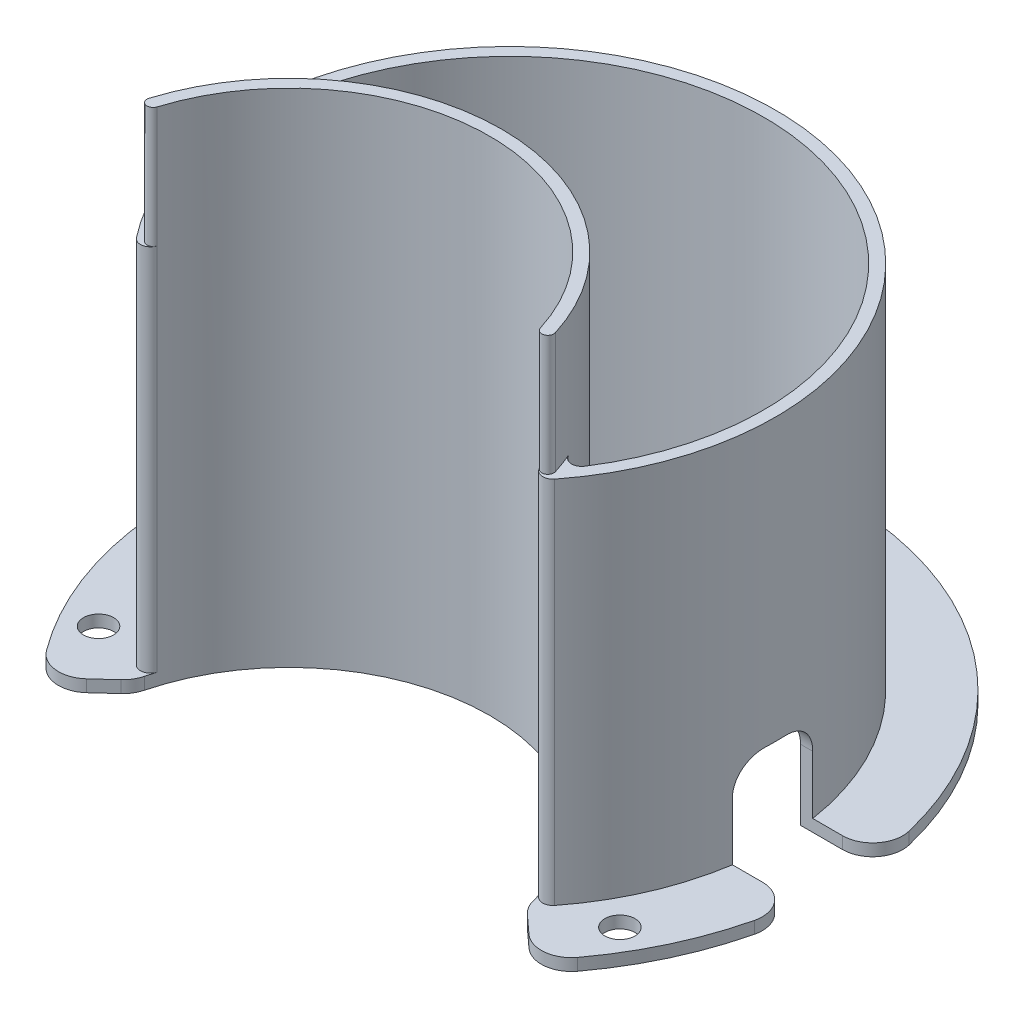
SolidWorks part; units mm, degrees
material "ABS"
ref_plane "Plan de face" through (0, 0, 0) normal (0, 0, 1) x (1, 0, 0)
ref_plane "Plan de dessus" through (0, 0, 0) normal (0, 1, 0) x (1, 0, 0)
ref_plane "Plan de droite" through (0, 0, 0) normal (1, 0, 0) x (0, 0, -1)
sketch "Esquisse1" plane through (0, 0, 0) normal (0, 1, 0) x (1, 0, 0)
  arc A0 (19.5688, -17.8693) -> (-19.5688, -17.8693) centre (0, 0) ccw
  arc A1 (19.5688, -17.8693) -> (-19.5688, -17.8693) centre (0, -22) ccw
  dimension "D1" = 53
  dimension "D2" = 2
  dimension "D3" = 40
extrude "Extru.-Mince1" add sketch "Esquisse1" along normal blind 38 thin thin type one direction reverse wall 1.2
sketch "Esquisse2" plane through (0, 0, 0) normal (0, 1, 0) x (1, 0, 0)
  line L0 (-19.5688, -17.8693) -> (-24.3687, -22.2524)
  line L1 (19.5688, -17.8693) -> (24.3687, -22.2524)
  arc A0 (19.5688, -17.8693) -> (-19.5688, -17.8693) centre (0, 0) ccw construction
  arc A1 (19.5688, -17.8693) -> (-19.5688, -17.8693) centre (0, 0) ccw
  arc A2 (24.3687, -22.2524) -> (-24.3687, -22.2524) centre (0, 0) ccw
  dimension "D1" = 33
extrude "Boss.-Extru.1" add sketch "Esquisse2" along normal blind 1.2
fillet "Congé1" radius 1 4 edges at (19.5688, 19.6, 17.8693) (-19.5688, 19.6, 17.8693) (20.1244, 19, 15.333) (-20.1244, 19, 15.333)
sketch "Esquisse3" plane through (0, 38, 0) normal (0, 1, 0) x (1, 0, 0)
  line L0 (0, 0) -> (0, -22) construction
  arc A0 (20.2411, -15.6962) -> (19.0954, -16.053) centre (19.6682, -15.8746) cw
  arc A1 (19.0954, -16.053) -> (-19.0954, -16.053) centre (0, -22) ccw construction
  arc A2 (19.4712, -13.6148) -> (-19.4712, -13.6148) centre (0, -22) ccw construction
  arc A3 (19.0954, -16.053) -> (-19.0954, -16.053) centre (0, -22) ccw
  arc A4 (20.2411, -15.6962) -> (-20.2411, -15.6962) centre (0, -22) ccw
  arc A5 (-20.2411, -15.6962) -> (-19.0954, -16.053) centre (-19.6682, -15.8746) ccw
  arc A7 (-20.8364, -16.3736) -> (-19.0954, -16.053) centre (-20.0501, -15.7557) ccw construction
extrude "Boss.-Extru.2" add sketch "Esquisse3" along normal blind 12
sketch "Esquisse4" plane through (0, 1.2, 0) normal (0, 1, 0) x (1, 0, 0)
  circle A0 centre (-25.9808, -15) radius 1.5
  circle A1 centre (0, 30) radius 1.5
  circle A2 centre (25.9808, -15) radius 1.5
  circle A3 centre (0, 0) radius 30 construction
  dimension "D1" = 120
  dimension "D2" = 3
  dimension "D3" = 60
extrude "Enlèv. mat.-Extru.1" cut sketch "Esquisse4" against normal through all
sketch "Esquisse5" plane through (0, 0, 0) normal (0, -1, 0) x (1, 0, 0)
  line L1 (24.9818, 4) -> (33, 4)
  line L2 (24.9818, 4) -> (24.9818, -4)
  line L3 (24.9818, -4) -> (33, -4)
  line L4 (33, 4) -> (33, -4)
  arc A0 (-21.2288, 13.7633) -> (21.2288, 13.7633) centre (0, 0) ccw construction
  arc A1 (-24.3687, 22.2524) -> (24.3687, 22.2524) centre (0, 0) ccw construction
  dimension "D1" = 8
extrude "Enlèv. mat.-Extru.2" cut sketch "Esquisse5" against normal blind 10
fillet "Congé2" radius 3 8 edges at (25.5891, 10, -4) (25.5891, 10, 4) (32.7567, 0.6, -4) (32.7567, 0.6, 4) (-24.3687, 0.6, 22.2524) (24.3687, 0.6, 22.2524) (19.5688, 0.6, 17.8693) (-19.5688, 0.6, 17.8693)
